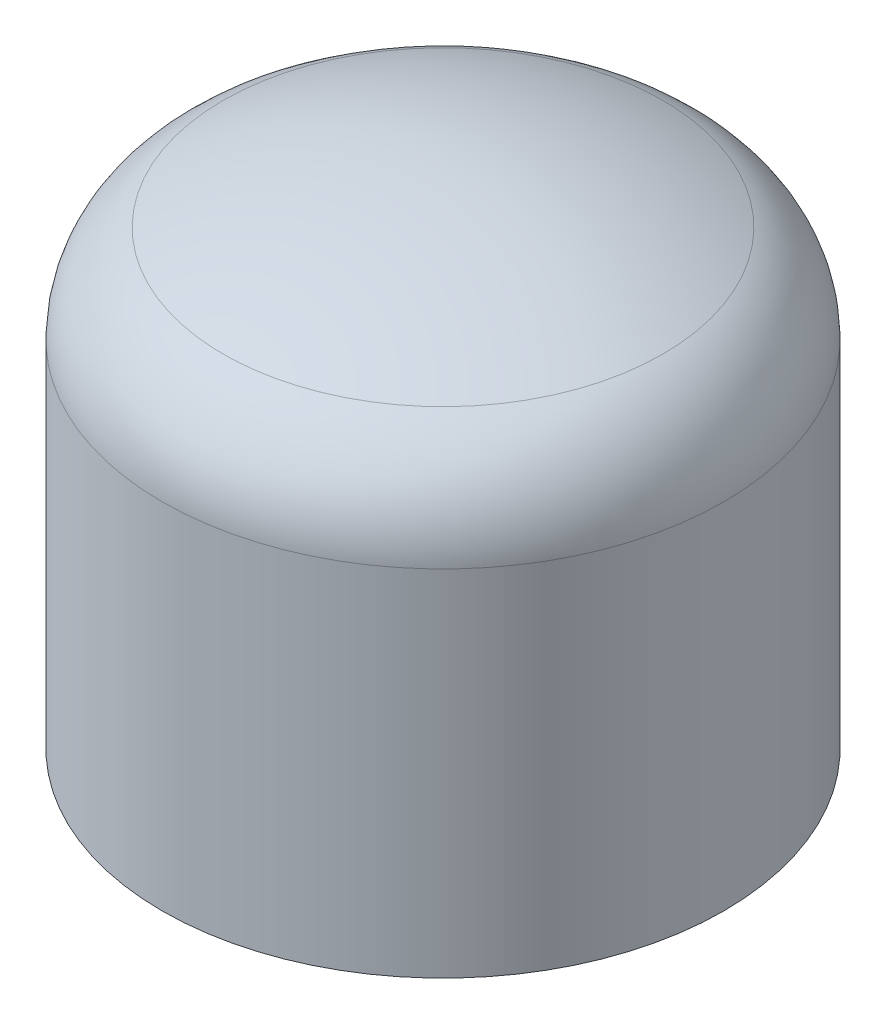
SolidWorks part; units mm, degrees
ref_plane "前视基准面" through (0, 0, 0) normal (0, 0, 1) x (1, 0, 0)
ref_plane "上视基准面" through (0, 0, 0) normal (0, 1, 0) x (1, 0, 0)
ref_plane "右视基准面" through (0, 0, 0) normal (1, 0, 0) x (0, 0, -1)
other "Configuration Table"
sketch "草图1" plane through (0, 0, 0) normal (0, 0, 1) x (1, 0, 0)
  line L0 (0, -83.8999) -> (0, 4111.0966) construction
  line L1 (-55, 71.9375) -> (-55, 0)
  line L2 (-57, 71.9375) -> (-57, 0)
  line L3 (-57, 0) -> (-55, 0)
  line L4 (0, 102) -> (0, 100)
  arc A0 (0, 100) -> (-43.75, 89.9218) centre (0, 0) ccw
  arc A1 (-55, 71.9375) -> (-43.75, 89.9218) centre (-35, 71.9375) cw
  arc A2 (0, 102) -> (-44.625, 91.7203) centre (0, 0) ccw
  arc A3 (-57, 71.9375) -> (-44.625, 91.7203) centre (-35, 71.9375) cw
  dimension "D1" = 200
  dimension "D3" = 20
  dimension "D2" = 110
  dimension "D4" = 100
  dimension "D5" = 2
revolve "旋转1" add sketch "草图1" angle 360 about L0
sketch "草图2" plane through (0, 0, 0) normal (0, -1, 0) x (1, 0, 0)
  circle A0 centre (0, 0) radius 55 construction
  circle A1 centre (0, 0) radius 55
  circle A2 centre (0, 0) radius 45
  circle A3 centre (0, 0) radius 50 construction
  circle A4 centre (0, 50) radius 2.25
  circle A5 centre (43.3013, -25) radius 2.25
  circle A6 centre (-43.3013, -25) radius 2.25
  point P13 (0, 0)
  dimension "D1" = 90
  dimension "D2" = 100
  dimension "D3" = 4.5
  dimension "D4" = 3
extrude "凸台-拉伸1" add sketch "草图2" against normal blind 2 from offset 30 offset against normal yes
sketch "草图3" plane through (0, 30, 0) normal (0, -1, 0) x (1, 0, 0)
  line L0 (0, 0) -> (-4.7936, 54.7907)
  line L1 (0, 0) -> (-55, 0)
  line L2 (0, -1000) -> (0, 49000) construction
  circle A0 centre (0, 0) radius 55 construction
  circle A1 centre (0, 0) radius 55 construction
  arc A2 (-4.7936, 54.7907) -> (-55, 0) centre (0, 0) ccw
  dimension "D1" = 5
  dimension "D2" = 90
extrude "切除-拉伸1" cut sketch "草图3" against normal up to next
